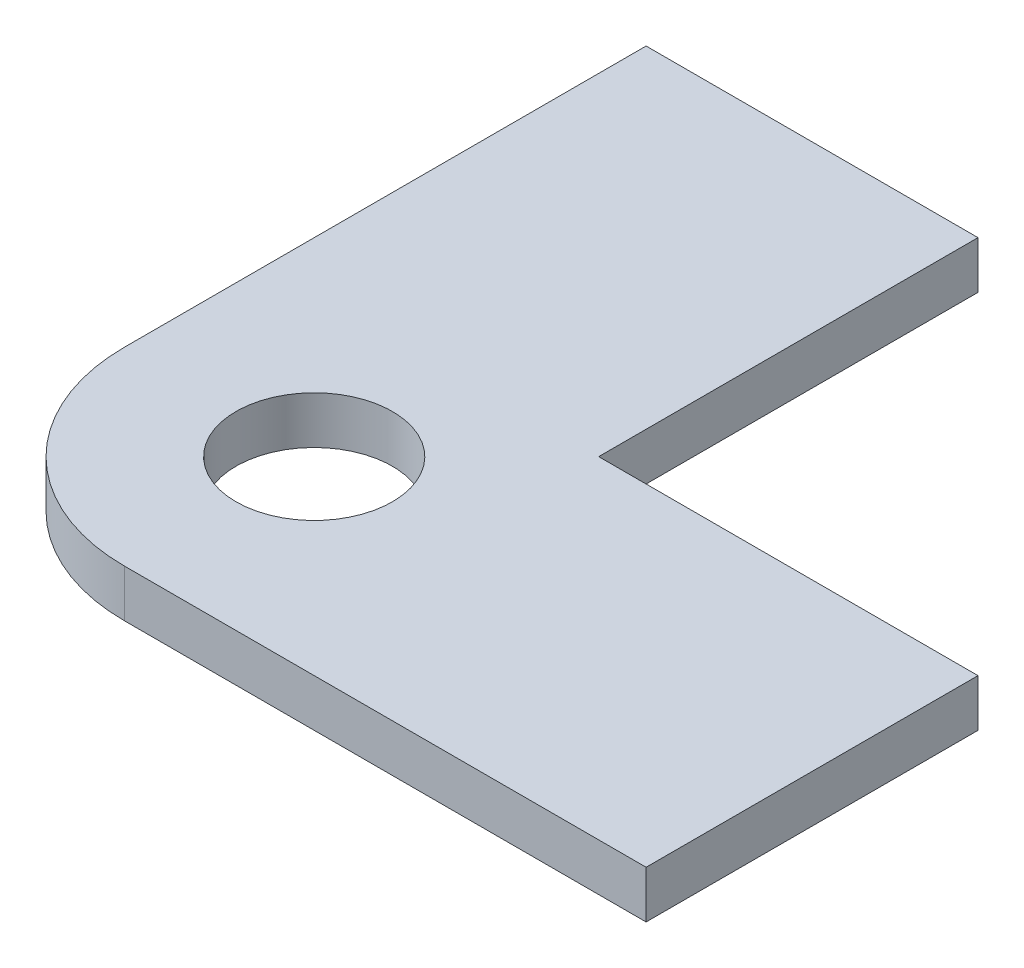
SolidWorks part; units mm, degrees
ref_plane "Front Plane" through (0, 0, 0) normal (0, 0, 1) x (1, 0, 0)
ref_plane "Top Plane" through (0, 0, 0) normal (0, 1, 0) x (1, 0, 0)
ref_plane "Right Plane" through (0, 0, 0) normal (1, 0, 0) x (0, 0, -1)
sketch "Sketch1" plane through (0, 0, 0) normal (0, 1, 0) x (1, 0, 0)
  line L0 (0, 0) -> (0, 11)
  line L1 (0, 0) -> (11, 0)
  line L2 (11, 0) -> (11, 3)
  line L3 (0, 11) -> (3, 11)
  line L4 (-3.9997, 0) -> (-3.9997, 11)
  line L5 (-3.9997, 11) -> (0, 11)
  line L6 (0, -3.9997) -> (11, -3.9997)
  line L7 (11, -3.9997) -> (11, 0)
  line L8 (3, 11) -> (3, 3)
  line L9 (3, 3) -> (11, 3)
  circle A0 centre (0, 0) radius 1.65
  arc A1 (0, -3.9997) -> (-3.9997, 0) centre (0, 0) cw
extrude "Boss-Extrude1" add sketch "Sketch1" along normal blind 1 contours A0 L1 L2 L9 L8 L3 L0 | A1 L6 L7 L1 A0 L0 L5 L4
